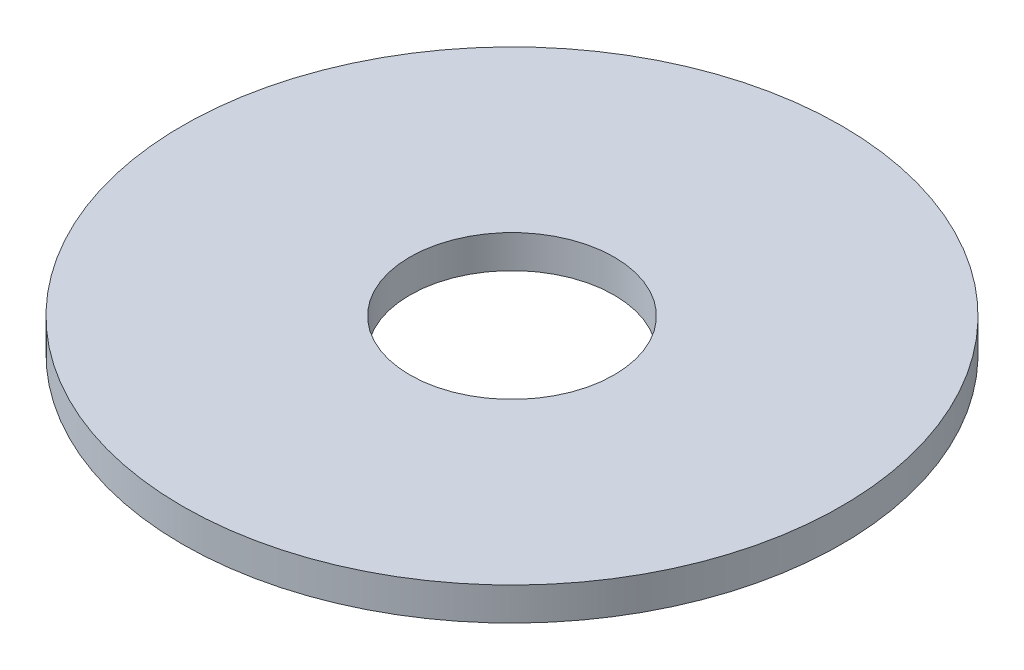
SolidWorks part; units mm, degrees
ref_plane "Front Plane" through (0, 0, 0) normal (0, 0, 1) x (1, 0, 0)
ref_plane "Top Plane" through (0, 0, 0) normal (0, 1, 0) x (1, 0, 0)
ref_plane "Right Plane" through (0, 0, 0) normal (1, 0, 0) x (0, 0, -1)
sketch "Sketch1" plane through (0, 0, 0) normal (0, 1, 0) x (1, 0, 0)
  circle A0 centre (0, 0) radius 10
  circle A1 centre (0, 0) radius 3.1
  dimension "D1" = 20
  dimension "D2" = 6.2
extrude "Boss-Extrude1" add sketch "Sketch1" along normal blind 1
